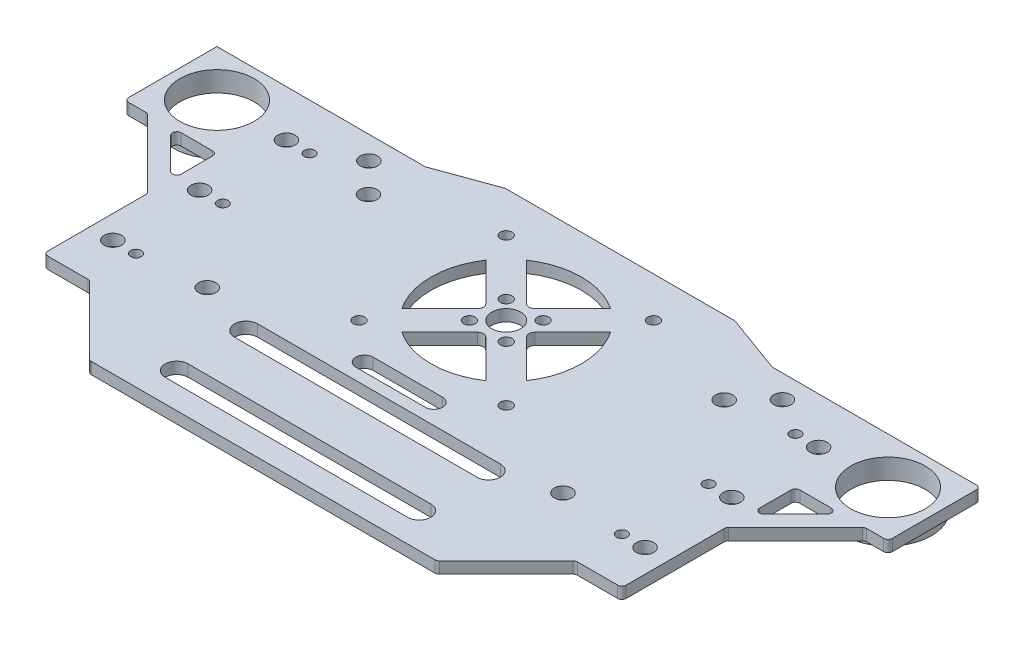
SolidWorks part; units mm, degrees
ref_plane "前视基准面" through (0, 0, 0) normal (0, 0, 1) x (1, 0, 0)
ref_plane "上视基准面" through (0, 0, 0) normal (0, 1, 0) x (1, 0, 0)
ref_plane "右视基准面" through (0, 0, 0) normal (1, 0, 0) x (0, 0, -1)
other "Configuration Table"
sketch "草图1" plane through (0, 0, 0) normal (0, 1, 0) x (1, 0, 0)
  line L0 (-50, 23) -> (50, 23)
  line L1 (50, 23) -> (50, -23)
  line L2 (50, -23) -> (-50, -23)
  line L3 (-50, -23) -> (-50, 23)
  line L5 (0, 23) -> (0, -23) construction
  line L6 (3.182, 10.182) -> (-3.182, 3.818) construction
  line L7 (7.253, 17.7886) -> (-10.7886, -0.253) construction
  line L8 (10.7886, 14.253) -> (-7.253, -3.7886) construction
  line L9 (10.7886, -0.253) -> (-7.253, 17.7886) construction
  line L10 (7.253, -3.7886) -> (-10.7886, 14.253) construction
  line L11 (-7.253, -3.7886) -> (10.7886, 14.253) construction
  line L12 (-10.7886, -0.253) -> (7.253, 17.7886) construction
  line L13 (-10.7886, 14.253) -> (7.253, -3.7886) construction
  line L14 (-7.253, 17.7886) -> (10.7886, -0.253) construction
  line L15 (10.7886, -0.253) -> (4.2426, 6.2929)
  line L16 (4.2426, 7.7071) -> (10.7886, 14.253)
  line L17 (7.253, 17.7886) -> (0.7071, 11.2426)
  line L18 (-0.7071, 11.2426) -> (-7.253, 17.7886)
  line L19 (-10.7886, 14.253) -> (-4.2426, 7.7071)
  line L20 (-4.2426, 6.2929) -> (-10.7886, -0.253)
  line L21 (-7.253, -3.7886) -> (-0.7071, 2.7574)
  line L22 (0.7071, 2.7574) -> (7.253, -3.7886)
  line L23 (-30, 23) -> (-19.848, 26.695)
  line L24 (-19.848, 26.695) -> (0.0265, 26.695)
  line L25 (30, 23) -> (19.848, 26.695)
  line L26 (19.848, 26.695) -> (-0.0265, 26.695)
  line L27 (-50, 23) -> (-66, 23)
  line L28 (-66, 23) -> (-66, 7)
  line L29 (-66, 7) -> (-50, 7)
  line L30 (-50, 7) -> (-50, 23)
  line L31 (-58, 7) -> (-50, -1)
  line L32 (-62, 7) -> (-50, -5)
  line L33 (-50, -1) -> (-50, -5)
  line L34 (-58, 7) -> (-62, 7)
  line L35 (58, 7) -> (62, 7)
  line L36 (50, -1) -> (50, -5)
  line L37 (62, 7) -> (50, -5)
  line L38 (58, 7) -> (50, -1)
  line L39 (50, 7) -> (50, 23)
  line L40 (66, 7) -> (50, 7)
  line L41 (66, 23) -> (66, 7)
  line L42 (50, 23) -> (66, 23)
  line L43 (-42, -23) -> (-30, -35)
  line L44 (-30, -35) -> (30, -35)
  line L45 (42, -23) -> (30, -35)
  line L46 (-42, -23) -> (42, -23)
  line L47 (-46, 23) -> (-46, -23) construction
  line L48 (-50, 0) -> (50, 0) construction
  line L49 (-6, -11.5) -> (6, -11.5) construction
  line L50 (-6, -10) -> (6, -10)
  line L51 (-20.9696, -17) -> (20.9696, -17) construction
  line L52 (-20.9696, -15) -> (20.9696, -15)
  line L53 (-20.9696, -19) -> (20.9696, -19)
  line L54 (-20.9696, -29) -> (20.9696, -29) construction
  line L55 (-20.9696, -27) -> (20.9696, -27)
  line L56 (-20.9696, -31) -> (20.9696, -31)
  line L57 (-6, -13) -> (6, -13)
  line L58 (-42, 15) -> (-42, 10.5355) construction
  circle A0 centre (0, 7) radius 2.5
  circle A1 centre (3.182, 10.182) radius 1
  circle A2 centre (3.182, 3.818) radius 1
  circle A3 centre (-3.182, 3.818) radius 1
  circle A4 centre (-3.182, 10.182) radius 1
  circle A5 centre (0, 7) radius 13
  circle A6 centre (12.7279, 19.7279) radius 1
  circle A7 centre (12.7279, -5.7279) radius 1
  circle A8 centre (-12.7279, -5.7279) radius 1
  circle A9 centre (-12.7279, 19.7279) radius 1
  arc A10 (-0.7071, 2.7574) -> (0.7071, 2.7574) centre (0, 2.0503) cw
  arc A11 (-4.2426, 7.7071) -> (-4.2426, 6.2929) centre (-4.9497, 7) cw
  arc A12 (0.7071, 11.2426) -> (-0.7071, 11.2426) centre (0, 11.9497) cw
  arc A13 (4.2426, 6.2929) -> (4.2426, 7.7071) centre (4.9497, 7) cw
  circle A15 centre (-58, 15) radius 6.425
  circle A16 centre (58, 15) radius 6.425
  circle A17 centre (-46, 15) radius 1.5
  circle A18 centre (-46, 0) radius 1.5
  circle A19 centre (-46, -15) radius 1.5
  circle A20 centre (46, -15) radius 1.5
  circle A21 centre (46, 0) radius 1.5
  circle A22 centre (46, 15) radius 1.5
  circle A23 centre (30.7465, 13.935) radius 1.5
  circle A24 centre (30.7465, -13.935) radius 1.5
  circle A25 centre (-30.7465, -13.935) radius 1.5
  circle A26 centre (-30.7465, 13.935) radius 1.5
  circle A27 centre (0, 7) radius 15
  arc A29 (-20.9696, -15) -> (-20.9696, -19) centre (-20.9696, -17) ccw
  arc A30 (20.9696, -19) -> (20.9696, -15) centre (20.9696, -17) ccw
  arc A31 (-20.9696, -27) -> (-20.9696, -31) centre (-20.9696, -29) ccw
  arc A32 (20.9696, -31) -> (20.9696, -27) centre (20.9696, -29) ccw
  arc A33 (-6, -10) -> (-6, -13) centre (-6, -11.5) ccw
  arc A34 (6, -13) -> (6, -10) centre (6, -11.5) ccw
  circle A35 centre (-42, 15) radius 0.925
  circle A36 centre (-42, 0) radius 0.925
  circle A37 centre (-42, -15) radius 0.925
  circle A38 centre (42, -15) radius 0.925
  circle A39 centre (42, 0) radius 0.925
  circle A40 centre (42, 15) radius 0.925
  circle A41 centre (35.7465, 19) radius 1.5
  circle A42 centre (-35.7465, 19) radius 1.5
  point P5 (50, 0)
  point P6 (0, 23)
  point P42 (0, 3.4645)
  point P45 (-3.5355, 7)
  point P48 (0, 10.5355)
  point P51 (3.5355, 7)
  point P64 (-58, 23)
  point P66 (-66, 15)
  point P84 (0, -35)
  point P92 (-50, 0)
  point P111 (0, -11.5)
  point P116 (0, -17)
  point P122 (0, -29)
  point P147 (0, 0)
  dimension "D3" = 5
  dimension "D4" = 2
  dimension "D8" = 26
  dimension "D9" = 2
  dimension "D13" = 1
  dimension "D18" = 16
  dimension "D19" = 16
  dimension "D20" = 12.85
  dimension "D26" = 3
  dimension "D27" = 4
  dimension "D28" = 3
  dimension "D29" = 3
  dimension "D32" = 3
  dimension "D35" = 30
  dimension "D36" = 1.5
  dimension "D44" = 1.85
  dimension "D49" = 3
  dimension "D1" = 100
  dimension "D2" = 46
  dimension "D6" = 9
  dimension "D7" = 45
  dimension "D11" = 18
  dimension "D14" = 16
  dimension "D15" = 20
  dimension "D16" = 20
  dimension "D17" = 3.695
  dimension "D21" = 4
  dimension "D22" = 45
  dimension "D23" = 8
  dimension "D24" = 45
  dimension "D25" = 12
  dimension "D30" = 15
  dimension "D31" = 15
  dimension "D33" = 61.493
  dimension "D34" = 27.87
  dimension "D37" = 6
  dimension "D38" = 12
  dimension "D39" = 6
  dimension "D40" = 2
  dimension "D41" = 2
  dimension "D42" = 20.9696
  dimension "D43" = 5.5
  dimension "D45" = 4
  dimension "D47" = 46
  dimension "D48" = 5
  dimension "D50" = 4
  dimension "D46" = 3
  dimension "D5" = 4
  dimension "D10" = 4
  dimension "D12" = 4
extrude "凸台-拉伸1" add sketch "草图1" along normal blind 2
fillet "圆角1" radius 0.75 19 edges at (66, 1, -23) (66, 1, -7) (62, 1, -7) (50, 1, 5) (50, 1, 23) (42, 1, 23) (30, 1, 35) (-30, 1, 35) (-42, 1, 23) (-50, 1, 23) (-50, 1, 5) (-62, 1, -7) (-66, 1, -7) (50, 1, -7) (50, 1, 1) (58, 1, -7) (-50, 1, 1) (-50, 1, -7) (-58, 1, -7)
sketch "草图2" plane through (0, 2, 0) normal (0, 1, 0) x (1, 0, 0)
  text T0 "M3" font "@Microsoft YaHei UI" height 2
  text T1 "M2" font "@Microsoft YaHei UI" height 2
  text T2 "M3" font "@Microsoft YaHei UI" height 2
sketch "草图3" plane through (0, 0, 0) normal (0, -1, 0) x (1, 0, 0)
  line L0 (0, 0) -> (0, -28.9381) construction
  circle A0 centre (-58, -15) radius 7.5
  circle A1 centre (58, -15) radius 7.5
  circle A3 centre (-58, -15) radius 6.425
  circle A4 centre (-58, -15) radius 6.425 construction
  circle A5 centre (58, -15) radius 6.425
  dimension "D1" = 15
extrude "凸台-拉伸2" add sketch "草图3" along normal blind 1.5
